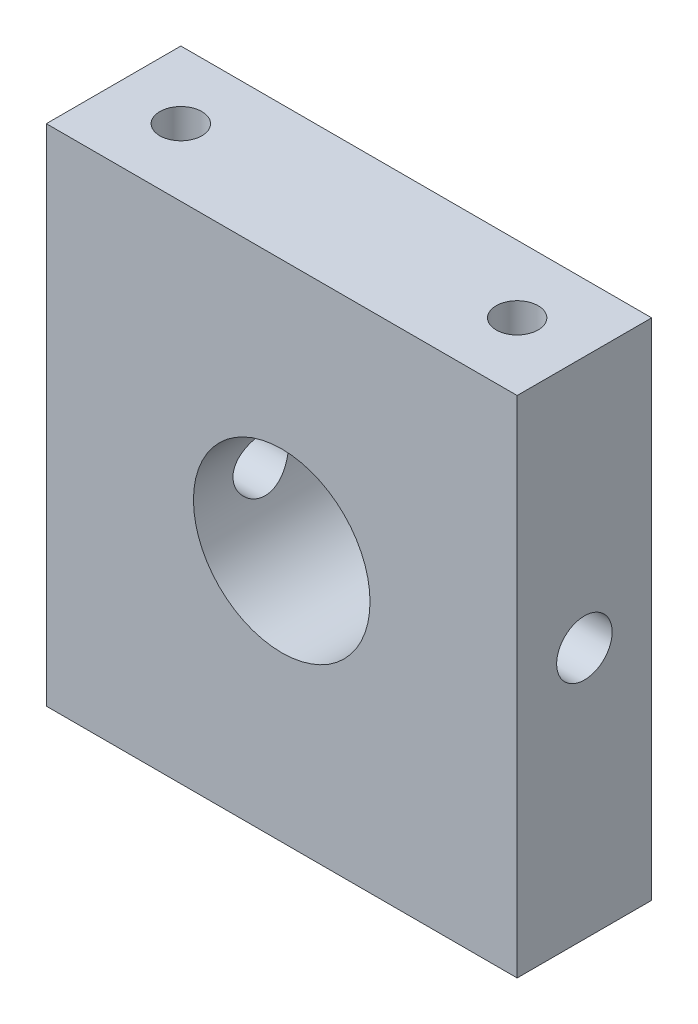
SolidWorks part; units mm, degrees
material "6061-O (SS)"
ref_plane "前视基准面" through (0, 0, 0) normal (0, 0, 1) x (1, 0, 0)
ref_plane "上视基准面" through (0, 0, 0) normal (0, 1, 0) x (1, 0, 0)
ref_plane "右视基准面" through (0, 0, 0) normal (1, 0, 0) x (0, 0, -1)
sketch "草图1" plane through (0, 0, 0) normal (0, 0, 1) x (1, 0, 0)
  line L1 (-14, -15) -> (14, -15)
  line L2 (-14, -15) -> (-14, 15)
  line L3 (-14, 15) -> (14, 15)
  line L4 (14, -15) -> (14, 15)
  line L5 (-14, -15) -> (14, 15) construction
  line L6 (-14, 15) -> (14, -15) construction
  circle A1 centre (0, 0) radius 5.25
  point P0 (0, 0)
  dimension "D3" = 10.5
  dimension "D1" = 30
  dimension "D2" = 28
extrude "凸台-拉伸1" add sketch "草图1" along normal blind 8
hole_wizard "M3 螺纹孔1" positions "草图2" profile "草图3" tap size "M3" standard "GB"
sketch "草图2" plane through (0, 15, 0) normal (0, 1, 0) x (1, 0, 0)
  line L0 (-10, -4) -> (10, -4)
  line L2 (14, -8) -> (14, 0) construction
  point P0 (-10, -4)
  point P2 (10, -4)
  point P8 (0, -4)
  point P12 (14, -4)
  dimension "D1" = 20
sketch "草图3" plane through (-10, 15, 4) normal (1, 0, 0) x (0, 0, 1)
  line L0 (0, 0) -> (0, 12.2511)
  line L1 (0, 12.2511) -> (1.25, 11.5)
  line L2 (1.25, 11.5) -> (1.25, 0)
  line L5 (1.25, 0) -> (0, 0)
  line L10 (0, 12.2511) -> (-1.25, 11.5) construction
  line L11 (0, -6.35) -> (0, 107.95) construction
  dimension "螺纹孔钻头直径" = 2.5
  dimension "螺纹孔钻头深度" = 11.5
  dimension "导头角度" = 118
cosmetic thread "孔螺蚊线1"
cosmetic thread "孔螺蚊线2"
hole_wizard "M3 螺纹孔2" positions "草图4" profile "草图5" tap size "M3" standard "GB"
sketch "草图4" plane through (0, -15, 0) normal (0, -1, 0) x (-1, 0, 0)
  line L0 (-10, -4) -> (10, -4)
  line L2 (14, -8) -> (14, 0) construction
  point P0 (10, -4)
  point P2 (-10, -4)
  point P9 (0, -4)
  point P12 (14, -4)
  dimension "D1" = 20
sketch "草图5" plane through (-10, -15, 4) normal (1, 0, 0) x (0, 0, -1)
  line L0 (0, 0) -> (0, 12.2511)
  line L1 (0, 12.2511) -> (1.25, 11.5)
  line L2 (1.25, 11.5) -> (1.25, 0)
  line L5 (1.25, 0) -> (0, 0)
  line L10 (0, 12.2511) -> (-1.25, 11.5) construction
  line L11 (0, -6.35) -> (0, 107.95) construction
  dimension "螺纹孔钻头直径" = 2.5
  dimension "螺纹孔钻头深度" = 11.5
  dimension "导头角度" = 118
cosmetic thread "孔螺蚊线3"
cosmetic thread "孔螺蚊线4"
hole_wizard "M4 螺纹孔1" positions "草图6" profile "草图7" tap size "M4" standard "GB" end condition through all
sketch "草图6" plane through (14, 0, 0) normal (1, 0, 0) x (0, 0, -1)
  line L1 (-8, -15) -> (0, -15) construction
  point P0 (-4, 0)
  point P10 (-4, -15)
cosmetic thread "孔螺蚊线5"
sketch "草图7" plane through (14, 0, 4) normal (0, 1, 0) x (0, 0, -1)
  line L0 (0, 0) -> (0, 28)
  line L1 (0, 28) -> (1.65, 28)
  line L2 (1.65, 28) -> (1.65, 0)
  line L5 (1.65, 0) -> (0, 0)
  line L11 (0, -6.35) -> (0, 107.95) construction
  dimension "通孔螺纹孔钻头直径" = 3.3
  dimension "通孔螺纹孔钻头深度" = 28
